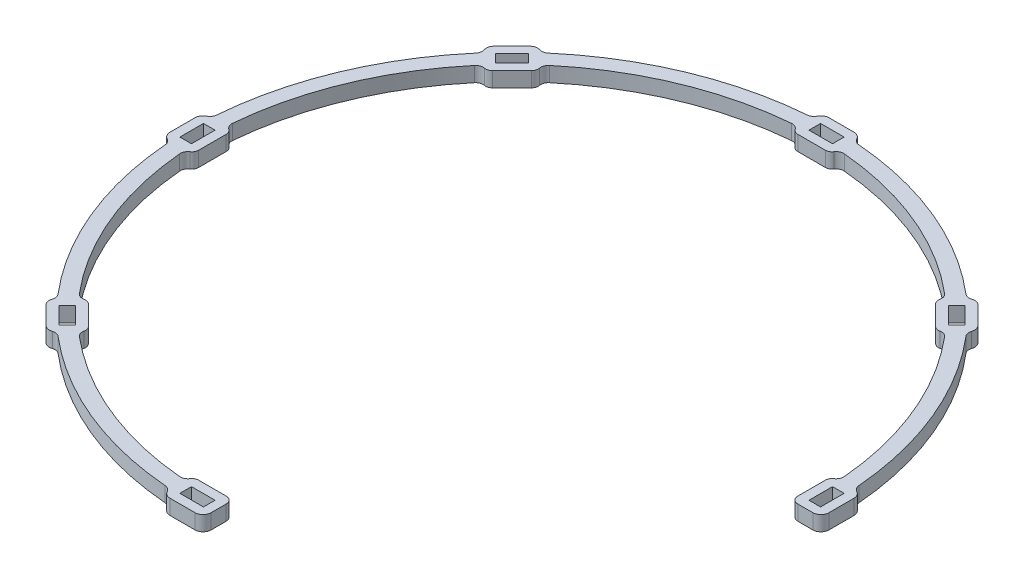
SolidWorks part; units mm, degrees
ref_plane "Front Plane" through (0, 0, 0) normal (0, 0, 1) x (1, 0, 0)
ref_plane "Top Plane" through (0, 0, 0) normal (0, 1, 0) x (1, 0, 0)
ref_plane "Right Plane" through (0, 0, 0) normal (1, 0, 0) x (0, 0, -1)
sketch "Sketch1" plane through (0, 0, 0) normal (0, 1, 0) x (1, 0, 0)
  line L0 (0, 0) -> (2.5, -85.9637) construction
  line L1 (0, 0) -> (85.9637, -2.5) construction
  line L2 (2.3837, -81.9653) -> (2.5, -85.9637)
  line L3 (81.9653, -2.3837) -> (85.9637, -2.5)
  arc A0 (85.9637, -2.5) -> (2.5, -85.9637) centre (0, 0) ccw
  arc A1 (81.9653, -2.3837) -> (2.3837, -81.9653) centre (0, 0) ccw
  dimension "D1" = 172
  dimension "D2" = 4
  dimension "D3" = 2.5
  dimension "D4" = 2.5
extrude "Boss-Extrude1" add sketch "Sketch1" along normal blind 4 contours A1 L2 A0 L3
sketch "Sketch5" plane through (0, 4, 0) normal (0, 1, 0) x (1, 0, 0)
  line L0 (0, -82) -> (0, -86) construction
  line L1 (-61.7413, -53.9631) -> (-64.5758, -56.7976)
  line L2 (-3.6847, -80) -> (3.6847, -80)
  line L3 (-5.5, -81.8153) -> (-5.5, -85.8239)
  line L4 (-3.3239, -88) -> (3.3239, -88)
  line L5 (5.5, -81.8153) -> (5.5, -85.8239)
  line L6 (-5.5, -80) -> (5.5, -88) construction
  line L7 (-5.5, -88) -> (5.5, -80) construction
  line L8 (-59.174, -53.9631) -> (-53.9631, -59.174)
  line L9 (-53.9631, -61.7413) -> (-56.7976, -64.5758)
  line L10 (-64.5758, -59.875) -> (-59.875, -64.5758)
  line L11 (-81.8153, 5.5) -> (-85.8239, 5.5)
  line L12 (-80, 3.6847) -> (-80, -3.6847)
  line L13 (-81.8153, -5.5) -> (-85.8239, -5.5)
  line L14 (-88, 3.3239) -> (-88, -3.3239)
  line L15 (-53.9631, 61.7413) -> (-56.7976, 64.5758)
  line L16 (-53.9631, 59.174) -> (-59.174, 53.9631)
  line L17 (-61.7413, 53.9631) -> (-64.5758, 56.7976)
  line L18 (-59.875, 64.5758) -> (-64.5758, 59.875)
  line L19 (5.5, 81.8153) -> (5.5, 85.8239)
  line L20 (3.6847, 80) -> (-3.6847, 80)
  line L21 (-5.5, 81.8153) -> (-5.5, 85.8239)
  line L22 (3.3239, 88) -> (-3.3239, 88)
  line L23 (61.7413, 53.9631) -> (64.5758, 56.7976)
  line L24 (59.174, 53.9631) -> (53.9631, 59.174)
  line L25 (53.9631, 61.7413) -> (56.7976, 64.5758)
  line L26 (64.5758, 59.875) -> (59.875, 64.5758)
  line L27 (81.8153, -5.5) -> (85.8239, -5.5)
  line L28 (80, -3.6847) -> (80, 3.6847)
  line L29 (81.8153, 5.5) -> (85.8239, 5.5)
  line L30 (88, -3.3239) -> (88, 3.3239)
  line L31 (53.9631, -61.7413) -> (56.7976, -64.5758) [skipped]
  line L32 (53.9631, -59.174) -> (59.174, -53.9631) [skipped]
  line L33 (61.7413, -53.9631) -> (64.5758, -56.7976) [skipped]
  line L34 (59.875, -64.5758) -> (64.5758, -59.875) [skipped]
  line L35 (0, 0) -> (3.6847, -80) construction
  arc A0 (81.9653, -2.3837) -> (2.3837, -81.9653) centre (0, 0) ccw construction
  arc A1 (85.9637, -2.5) -> (2.5, -85.9637) centre (0, 0) ccw construction
  circle A2 centre (0, 0) radius 84 construction
  arc A3 (-5.5, -85.8239) -> (-3.3239, -88) centre (-3.3239, -85.8239) ccw
  arc A4 (3.6847, -80) -> (5.5, -81.8153) centre (3.6847, -81.8153) cw
  arc A5 (3.3239, -88) -> (5.5, -85.8239) centre (3.3239, -85.8239) ccw
  arc A6 (-3.6847, -80) -> (-5.5, -81.8153) centre (-3.6847, -81.8153) ccw
  arc A7 (-59.174, -53.9631) -> (-61.7413, -53.9631) centre (-60.4576, -55.2467) ccw
  arc A8 (-64.5758, -56.7976) -> (-64.5758, -59.875) centre (-63.0371, -58.3363) ccw
  arc A9 (-53.9631, -59.174) -> (-53.9631, -61.7413) centre (-55.2467, -60.4576) cw
  arc A10 (-59.875, -64.5758) -> (-56.7976, -64.5758) centre (-58.3363, -63.0371) ccw
  arc A11 (-80, 3.6847) -> (-81.8153, 5.5) centre (-81.8153, 3.6847) ccw
  arc A12 (-85.8239, 5.5) -> (-88, 3.3239) centre (-85.8239, 3.3239) ccw
  arc A13 (-80, -3.6847) -> (-81.8153, -5.5) centre (-81.8153, -3.6847) cw
  arc A14 (-88, -3.3239) -> (-85.8239, -5.5) centre (-85.8239, -3.3239) ccw
  arc A15 (-53.9631, 59.174) -> (-53.9631, 61.7413) centre (-55.2467, 60.4576) ccw
  arc A16 (-56.7976, 64.5758) -> (-59.875, 64.5758) centre (-58.3363, 63.0371) ccw
  arc A17 (-59.174, 53.9631) -> (-61.7413, 53.9631) centre (-60.4576, 55.2467) cw
  arc A18 (-64.5758, 59.875) -> (-64.5758, 56.7976) centre (-63.0371, 58.3363) ccw
  arc A19 (3.6847, 80) -> (5.5, 81.8153) centre (3.6847, 81.8153) ccw
  arc A20 (5.5, 85.8239) -> (3.3239, 88) centre (3.3239, 85.8239) ccw
  arc A21 (-3.6847, 80) -> (-5.5, 81.8153) centre (-3.6847, 81.8153) cw
  arc A22 (-3.3239, 88) -> (-5.5, 85.8239) centre (-3.3239, 85.8239) ccw
  arc A23 (59.174, 53.9631) -> (61.7413, 53.9631) centre (60.4576, 55.2467) ccw
  arc A24 (64.5758, 56.7976) -> (64.5758, 59.875) centre (63.0371, 58.3363) ccw
  arc A25 (53.9631, 59.174) -> (53.9631, 61.7413) centre (55.2467, 60.4576) cw
  arc A26 (59.875, 64.5758) -> (56.7976, 64.5758) centre (58.3363, 63.0371) ccw
  arc A27 (80, -3.6847) -> (81.8153, -5.5) centre (81.8153, -3.6847) ccw
  arc A28 (85.8239, -5.5) -> (88, -3.3239) centre (85.8239, -3.3239) ccw
  arc A29 (80, 3.6847) -> (81.8153, 5.5) centre (81.8153, 3.6847) cw
  arc A30 (88, 3.3239) -> (85.8239, 5.5) centre (85.8239, 3.3239) ccw
  arc A31 (53.9631, -59.174) -> (53.9631, -61.7413) centre (55.2467, -60.4576) ccw [skipped]
  arc A32 (56.7976, -64.5758) -> (59.875, -64.5758) centre (58.3363, -63.0371) ccw [skipped]
  arc A33 (59.174, -53.9631) -> (61.7413, -53.9631) centre (60.4576, -55.2467) cw [skipped]
  arc A34 (64.5758, -59.875) -> (64.5758, -56.7976) centre (63.0371, -58.3363) ccw [skipped]
  point P9 (0, -84)
  point P13 (0, -84)
  dimension "D3" = 8
  dimension "D1" = 8
  dimension "D2" = 11
extrude "Boss-Extrude2" add sketch "Sketch5" against normal up to surface (4 mm away) up to face at (-8.0969, 0, -8.0969)
sketch "Sketch3" plane through (0, 4, 0) normal (0, 1, 0) x (1, 0, 0)
  line L0 (-62.7204, -58.2656) -> (-58.2656, -62.7204)
  line L1 (-3.15, -82.45) -> (3.15, -82.45)
  line L2 (-3.15, -82.45) -> (-3.15, -85.55)
  line L3 (-3.15, -85.55) -> (3.15, -85.55)
  line L4 (3.15, -82.45) -> (3.15, -85.55)
  line L5 (-3.15, -82.45) -> (3.15, -85.55) construction
  line L6 (-3.15, -85.55) -> (3.15, -82.45) construction
  line L7 (-56.0736, -60.5283) -> (-58.2656, -62.7204)
  line L8 (-60.5283, -56.0736) -> (-56.0736, -60.5283)
  line L9 (-60.5283, -56.0736) -> (-62.7204, -58.2656)
  line L10 (-85.55, 3.15) -> (-85.55, -3.15)
  line L11 (-82.45, -3.15) -> (-85.55, -3.15)
  line L12 (-82.45, 3.15) -> (-82.45, -3.15)
  line L13 (-82.45, 3.15) -> (-85.55, 3.15)
  line L14 (-58.2656, 62.7204) -> (-62.7204, 58.2656)
  line L15 (-60.5283, 56.0736) -> (-62.7204, 58.2656)
  line L16 (-56.0736, 60.5283) -> (-60.5283, 56.0736)
  line L17 (-56.0736, 60.5283) -> (-58.2656, 62.7204)
  line L18 (3.15, 85.55) -> (-3.15, 85.55)
  line L19 (-3.15, 82.45) -> (-3.15, 85.55)
  line L20 (3.15, 82.45) -> (-3.15, 82.45)
  line L21 (3.15, 82.45) -> (3.15, 85.55)
  line L22 (62.7204, 58.2656) -> (58.2656, 62.7204)
  line L23 (56.0736, 60.5283) -> (58.2656, 62.7204)
  line L24 (60.5283, 56.0736) -> (56.0736, 60.5283)
  line L25 (60.5283, 56.0736) -> (62.7204, 58.2656)
  line L26 (85.55, -3.15) -> (85.55, 3.15)
  line L27 (82.45, 3.15) -> (85.55, 3.15)
  line L28 (82.45, -3.15) -> (82.45, 3.15)
  line L29 (82.45, -3.15) -> (85.55, -3.15)
  line L30 (58.2656, -62.7204) -> (62.7204, -58.2656) [skipped]
  line L31 (60.5283, -56.0736) -> (62.7204, -58.2656) [skipped]
  line L32 (56.0736, -60.5283) -> (60.5283, -56.0736) [skipped]
  line L33 (56.0736, -60.5283) -> (58.2656, -62.7204) [skipped]
  line L34 (0, 0) -> (3.15, -82.45) construction
  point P0 (0, -84)
  dimension "D1" = 6.3
  dimension "D2" = 3.1
  dimension "D3" = 8
extrude "Cut-Extrude1" cut sketch "Sketch3" against normal up to next
fillet "Fillet1" radius 2 24 edges at (-85.8239, 2, 5.5) (-56.7976, 2, 64.5758) (-5.5, 2, 85.8239) (81.8153, 2, -5.5) (53.9631, 2, -61.7413) (61.7413, 2, -53.9631) (-5.5, 2, -81.8153) (-5.5, 2, 81.8153) (-64.5758, 2, 56.7976) (-85.8239, 2, -5.5) (-64.5758, 2, -56.7976) (-56.7976, 2, -64.5758) (-5.5, 2, -85.8239) (-61.7413, 2, 53.9631) (-81.8153, 2, -5.5) (5.5, 2, -85.8239) (56.7976, 2, -64.5758) (-53.9631, 2, 61.7413) (85.8239, 2, -5.5) (64.5758, 2, -56.7976) (5.5, 2, -81.8153) (-53.9631, 2, -61.7413) (-61.7413, 2, -53.9631) (-81.8153, 2, 5.5)
